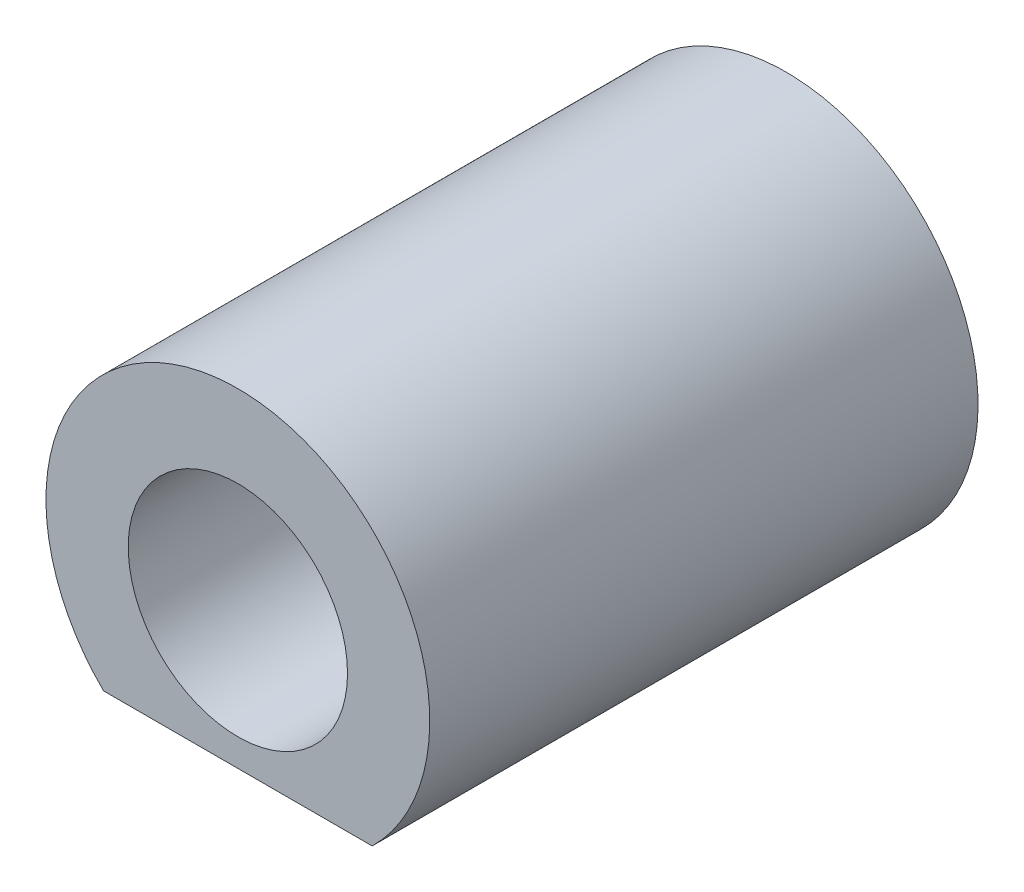
SolidWorks part; units mm, degrees
ref_plane "Front Plane" through (0, 0, 0) normal (0, 0, 1) x (1, 0, 0)
ref_plane "Top Plane" through (0, 0, 0) normal (0, 1, 0) x (1, 0, 0)
ref_plane "Right Plane" through (0, 0, 0) normal (1, 0, 0) x (0, 0, -1)
sketch "Sketch1" plane through (0, 0, 0) normal (0, 0, 1) x (1, 0, 0)
  line L0 (4.899, -5) -> (-4.899, -5) construction
  line L1 (4.899, -5) -> (-4.899, -5)
  arc A0 (4.899, -5) -> (-4.899, -5) centre (0, 0) ccw construction
  arc A1 (4.899, -5) -> (-4.899, -5) centre (0, 0) ccw
  circle A2 centre (0, 0) radius 4
extrude "Boss-Extrude1" add sketch "Sketch1" against normal up to surface (20 mm away)
